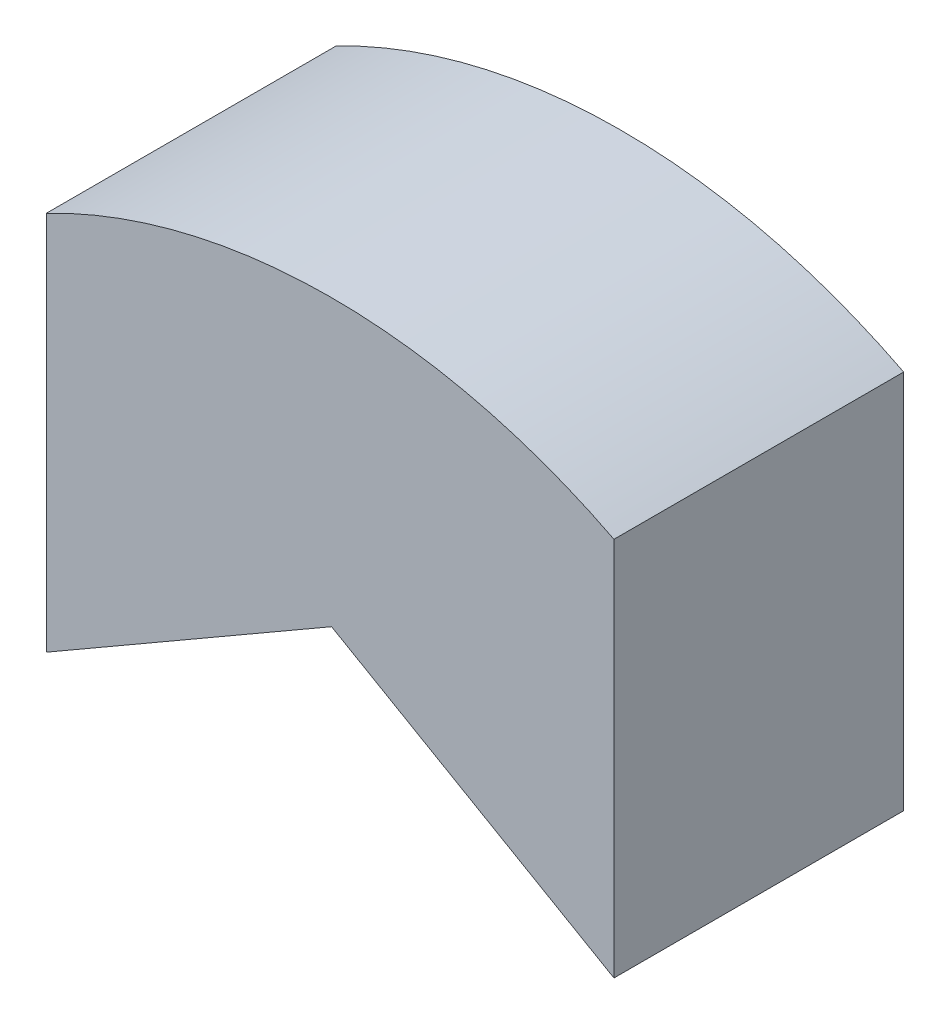
SolidWorks part; units mm, degrees
ref_plane "Front Plane" through (0, 0, 0) normal (0, 0, 1) x (1, 0, 0)
ref_plane "Top Plane" through (0, 0, 0) normal (0, 1, 0) x (1, 0, 0)
ref_plane "Right Plane" through (0, 0, 0) normal (1, 0, 0) x (0, 0, -1)
sketch "Sketch1" plane through (0, 0, 0) normal (0, 0, 1) x (1, 0, 0)
  line L0 (-6.5, 3.7528) -> (-6.5, 12.2866) construction
  line L3 (6.3355, 3.8478) -> (0, 7.5056)
  line L4 (0, 7.5056) -> (-6.4, 3.8105)
  line L7 (6.4355, 3.79) -> (6.4355, 12.3205) construction
  line L8 (-6.4, 12.339) -> (-6.4, 3.8105)
  line L9 (-3.25, -5.6292) -> (0, -7.5056) [skipped]
  line L10 (3.25, -5.6292) -> (6.5, -3.7528) [skipped]
  line L11 (6.5, 0) -> (6.5, 3.7528) [skipped]
  line L12 (6.3355, 3.8478) -> (6.3355, 12.3722)
  line L14 (-6.5, 3.7528) -> (-6.5, 0) [skipped]
  arc A0 (6.3355, 12.3722) -> (-6.4, 12.339) centre (0, 0) ccw
  circle A1 centre (0, 0) radius 6.5 construction
  dimension "D1" = 27.8
  dimension "D2" = 0.1
  dimension "D3" = 0.1
extrude "Boss-Extrude1" add sketch "Sketch1" along normal blind 6.5
